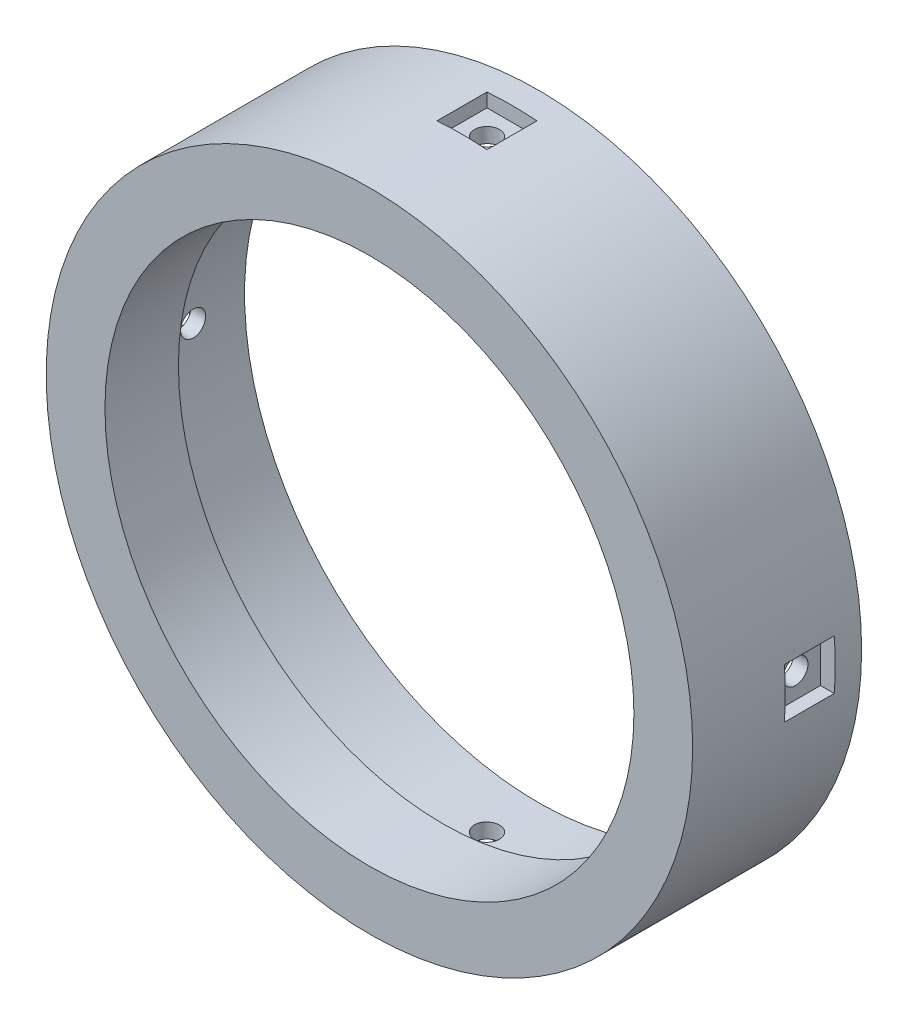
SolidWorks part; units mm, degrees
ref_plane "Alzado" through (0, 0, 0) normal (0, 0, 1) x (1, 0, 0)
ref_plane "Planta" through (0, 0, 0) normal (0, 1, 0) x (1, 0, 0)
ref_plane "Vista lateral" through (0, 0, 0) normal (1, 0, 0) x (0, 0, -1)
sketch "Croquis1" plane through (0, 0, 0) normal (0, 0, 1) x (1, 0, 0)
  circle A0 centre (0, 0) radius 44
  circle A1 centre (0, 0) radius 40
extrude "Manga" add sketch "Croquis1" along normal blind 13
sketch "Croquis2" plane through (0, 0, 13) normal (0, 0, 1) x (1, 0, 0)
  circle A0 centre (0, 0) radius 44
  circle A1 centre (0, 0) radius 36
extrude "Labio" add sketch "Croquis2" along normal blind 10
sketch "Croquis3" plane through (0, 0, 0) normal (0, 1, 0) x (1, 0, 0)
  circle A0 centre (0, -7) radius 1.7
extrude "Pasantes_M3_radiales_A" cut sketch "Croquis3" against normal through all and the other way through all
sketch "Croquis4" plane through (0, 0, 0) normal (1, 0, 0) x (0, 0, -1)
  circle A0 centre (-7, 0) radius 1.7
extrude "Pasantes_M3_radiales_B" cut sketch "Croquis4" against normal through all and the other way through all
ref_plane "Plano_caja_0" through (42, 0, 0) normal (1, 0, 0) x (0, 0, -1)
sketch "Croquis5" plane through (42, 0, 0) normal (1, 0, 0) x (0, 0, -1)
  circle A0 centre (-7, 0) radius 3.25
ref_plane "Plano_caja_90" through (0, 42, 0) normal (0, 1, 0) x (1, 0, 0)
sketch "Croquis6" plane through (0, 42, 0) normal (0, 1, 0) x (1, 0, 0)
  circle A0 centre (0, -7) radius 3.25
ref_plane "Plano_caja_180" through (-42, 0, 0) normal (1, 0, 0) x (0, 0, -1)
sketch "Croquis7" plane through (-42, 0, 0) normal (1, 0, 0) x (0, 0, -1)
  circle A0 centre (-7, 0) radius 3.25
ref_plane "Plano_caja_270" through (0, -42, 0) normal (0, 1, 0) x (1, 0, 0)
sketch "Croquis8" plane through (0, -42, 0) normal (0, 1, 0) x (1, 0, 0)
  circle A0 centre (0, -7) radius 3.25
ref_plane "Plano_planos_M3" through (0, 0, 3.6) normal (0, 0, 1) x (1, 0, 0)
sketch "Croquis10" plane through (0, 0, 3.6) normal (0, 0, 1) x (1, 0, 0)
  line L0 (42, -3.4) -> (45.5, -3.4)
  line L1 (45.5, -3.4) -> (45.5, 3.4)
  line L2 (45.5, 3.4) -> (42, 3.4)
  line L3 (42, 3.4) -> (42, -3.4)
  line L4 (3.4, 42) -> (3.4, 45.5)
  line L5 (3.4, 45.5) -> (-3.4, 45.5)
  line L6 (-3.4, 45.5) -> (-3.4, 42)
  line L7 (-3.4, 42) -> (3.4, 42)
  line L8 (-42, 3.4) -> (-45.5, 3.4)
  line L9 (-45.5, 3.4) -> (-45.5, -3.4)
  line L10 (-45.5, -3.4) -> (-42, -3.4)
  line L11 (-42, -3.4) -> (-42, 3.4)
  line L12 (-3.4, -42) -> (-3.4, -45.5)
  line L13 (-3.4, -45.5) -> (3.4, -45.5)
  line L14 (3.4, -45.5) -> (3.4, -42)
  line L15 (3.4, -42) -> (-3.4, -42)
extrude "Planos_M3_tornillos" cut sketch "Croquis10" along normal blind 6.8
